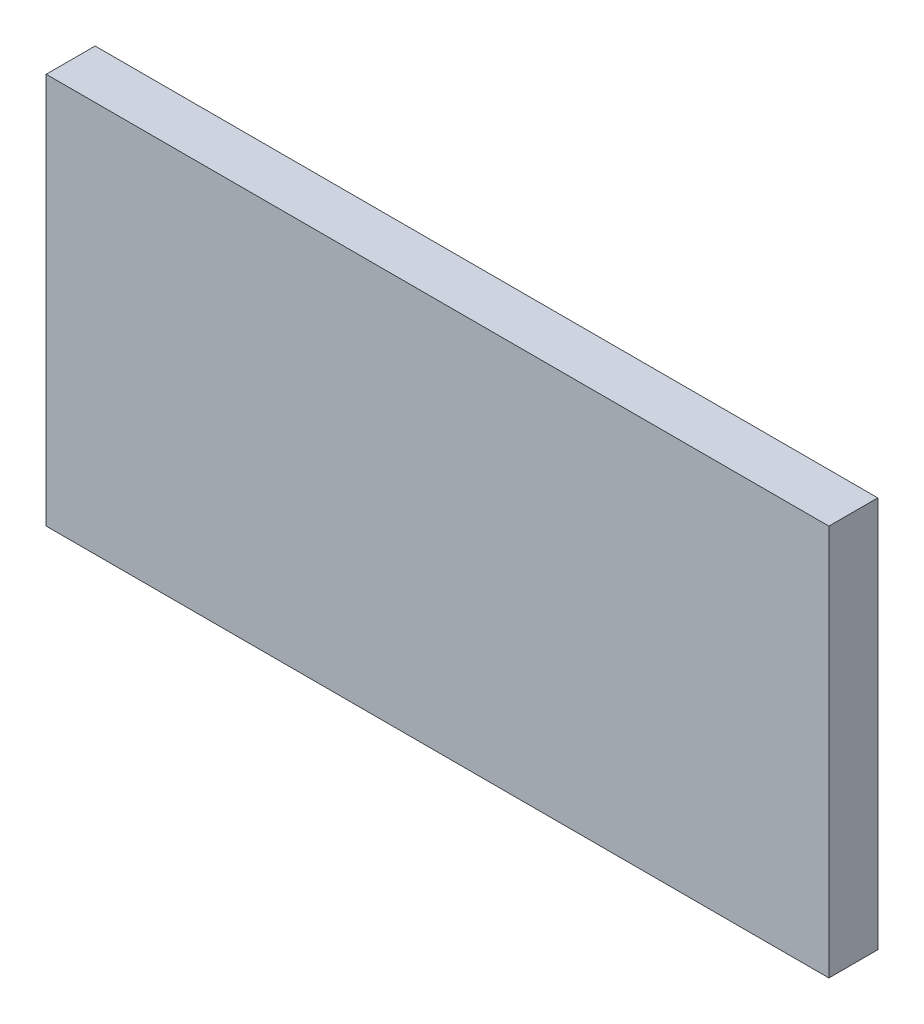
SolidWorks part; units mm, degrees
ref_plane "Front Plane" through (0, 0, 0) normal (0, 0, 1) x (1, 0, 0)
ref_plane "Top Plane" through (0, 0, 0) normal (0, 1, 0) x (1, 0, 0)
ref_plane "Right Plane" through (0, 0, 0) normal (1, 0, 0) x (0, 0, -1)
sketch "Sketch1" plane through (0, 0, 0) normal (0, 0, 1) x (1, 0, 0)
  line L1 (0, 0) -> (50.8, 0)
  line L2 (0, 0) -> (0, 25.4)
  line L3 (0, 25.4) -> (50.8, 25.4)
  line L4 (50.8, 0) -> (50.8, 25.4)
  dimension "D1" = 50.8
  dimension "D2" = 25.4
extrude "Boss-Extrude1" add sketch "Sketch1" along normal blind 3.175
